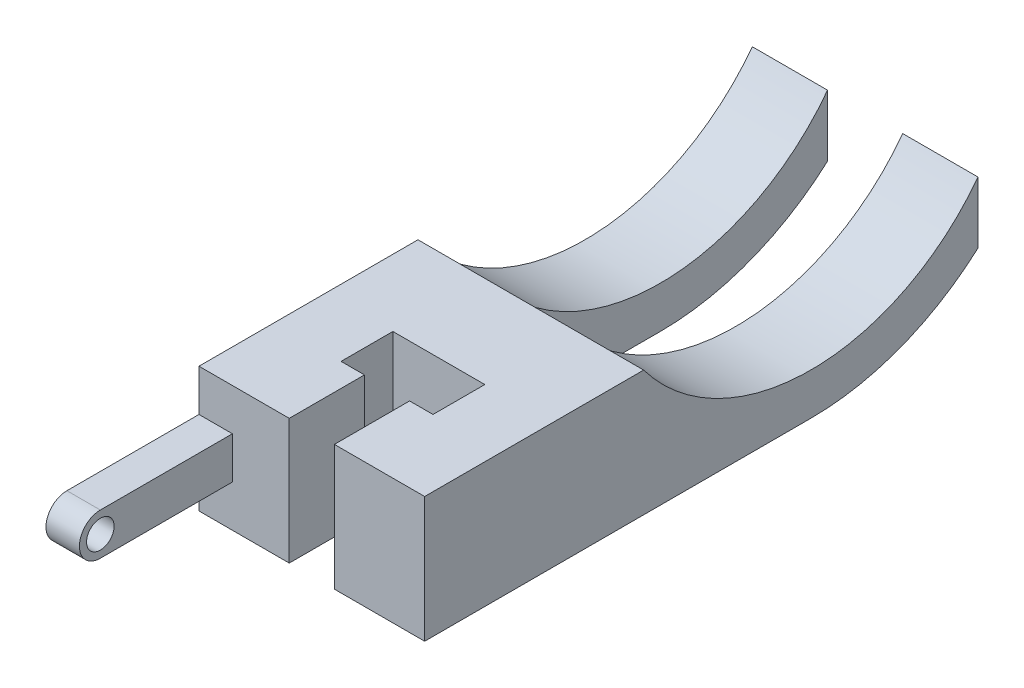
SolidWorks part; units mm, degrees
ref_plane "前视基准面" through (0, 0, 0) normal (0, 0, 1) x (1, 0, 0)
ref_plane "上视基准面" through (0, 0, 0) normal (0, 1, 0) x (1, 0, 0)
ref_plane "右视基准面" through (0, 0, 0) normal (1, 0, 0) x (0, 0, -1)
sketch "草图1" plane through (0, 0, 0) normal (0, 1, 0) x (1, 0, 0)
  line L0 (-5.5, 0) -> (5.5, 0)
  line L1 (5.5, 0) -> (5.5, -6.2)
  line L2 (5.5, -6.2) -> (2.7, -6.2)
  line L3 (2.7, -6.2) -> (2.7, -9.2)
  line L4 (2.7, -9.2) -> (5.5, -9.2)
  line L5 (5.5, -9.2) -> (5.5, -17)
  line L6 (5.5, -17) -> (8.5, -17)
  line L8 (-8.5, 3) -> (8.5, 3)
  line L9 (8.5, 3) -> (8.5, -17)
  line L10 (-5.5, -17) -> (-8.5, -17)
  line L11 (-5.5, -9.2) -> (-5.5, -17)
  line L12 (-2.7, -9.2) -> (-5.5, -9.2)
  line L13 (-2.7, -6.2) -> (-2.7, -9.2)
  line L14 (-5.5, -6.2) -> (-2.7, -6.2)
  line L15 (-5.5, 0) -> (-5.5, -6.2)
  line L16 (-8.5, 3) -> (-8.5, -17)
extrude "凸台-拉伸2" add sketch "草图1" along normal blind 15
sketch "草图2" plane through (8.5, 0, 0) normal (1, 0, 0) x (0, 0, -1)
  line L0 (-17, 15) -> (-17, 10)
  line L1 (-17, 15) -> (-17, 0) construction
  line L2 (-17, 0) -> (-17, 5)
  line L3 (-17, 15) -> (-9.2, 15)
  line L4 (-17, 15) -> (3, 15) construction
  line L5 (-9.2, 15) -> (-9.2, 10)
  line L6 (-9.2, 10) -> (-17, 10)
  line L7 (-17, 5) -> (-9.2, 5)
  line L8 (-9.2, 5) -> (-9.2, 0)
  line L9 (-17, 0) -> (3, 0) construction
  line L10 (-9.2, 0) -> (-17, 0)
extrude "切除-拉伸1" cut sketch "草图2" against normal blind 23
sketch "草图3" plane through (-8.5, 0, 0) normal (-1, 0, 0) x (0, 0, 1)
  line L0 (-3, 15) -> (-3, 7.5)
  line L1 (-3, 15) -> (-3, 0) construction
  line L2 (-3, 7.5) -> (15, 7.5)
  circle A0 centre (15, 7.5) radius 1.65
extrude "切除-拉伸2" cut sketch "草图3" against normal blind 23
sketch "草图4" plane through (0, 0, 17) normal (0, 0, 1) x (1, 0, 0)
  line L0 (-8.5, 10) -> (-5.5, 10)
  line L1 (-8.5, 10) -> (-8.5, 5.005)
  line L2 (-5.5, 10) -> (-5.5, 5.005)
  line L3 (-8.5, 5.005) -> (-5.5, 5.005)
  line L4 (-5.5, 10) -> (-5.5, 5) construction
  line L5 (-8.5, 10) -> (-5.5, 10) construction
  line L6 (5.5, 10) -> (8.5, 10)
  line L7 (5.5, 10) -> (5.5, 4.9814)
  line L8 (8.5, 10) -> (8.5, 4.9814)
  line L9 (5.5, 4.9814) -> (8.5, 4.9814)
extrude "凸台-拉伸3" add sketch "草图4" along normal blind 0.5
sketch "草图5" plane through (-8.5, 0, 0) normal (-1, 0, 0) x (0, 0, 1)
  line L0 (15, 10) -> (17.5, 10)
  line L1 (17.5, 10) -> (17.5, 7.5)
  line L2 (17.5, 7.5) -> (17.5, 5.005)
  line L3 (17.5, 5.005) -> (15, 5)
  line L4 (17.5, 5.005) -> (17.7329, 2.2884)
  line L5 (17.7329, 2.2884) -> (15, 5)
  circle A0 centre (15, 7.5) radius 2.5
extrude "切除-拉伸4" cut sketch "草图5" against normal blind 20.5
sketch "草图7" plane through (-8.5, 0, 0) normal (-1, 0, 0) x (0, 0, 1)
  line L0 (-3, 15) -> (-3, 0)
  line L1 (-3, 0) -> (-18, 0)
  line L2 (-18, 0) -> (-3, 15)
extrude "凸台-拉伸4" add sketch "草图7" against normal blind 17
sketch "草图8" plane through (0, 15, 0) normal (0, 1, 0) x (1, 0, 0)
  line L0 (-8.5, 3) -> (-8.5, 5)
  line L1 (-8.5, 3) -> (-8.5, 18) construction
  line L2 (-8.5, 5) -> (-6.5, 5)
  line L3 (-6.5, 5) -> (-6.5, 18)
  line L4 (-6.5, 5) -> (8.5, 5)
  line L5 (8.5, 3) -> (8.5, 18) construction
  line L6 (8.5, 5) -> (6.5, 5)
  line L7 (6.5, 5) -> (6.5, 18)
  line L8 (6.5, 18) -> (-6.5, 18)
extrude "切除-拉伸5" cut sketch "草图8" against normal blind 14 contours L7 L8 L3 L4
sketch "草图9" plane through (0, 1, 0) normal (0, 1, 0) x (1, 0, 0)
  line L0 (0, 5) -> (0, 8)
  line L1 (-6.5, 5) -> (6.5, 5) construction
  line L2 (0, 8) -> (-4, 8)
  circle A0 centre (-4, 8) radius 1.65
  circle A1 centre (4, 8) radius 1.65
  circle A2 centre (-4, 14) radius 1.65
  circle A3 centre (4, 14) radius 1.65
  dimension "D1" = 2
extrude "切除-拉伸6" cut sketch "草图9" against normal blind 14
sketch "草图10" plane through (-8.5, 0, 0) normal (-1, 0, 0) x (0, 0, 1)
  line L0 (15, 10) -> (25, 10)
  line L2 (15, 5) -> (25, 5)
  line L3 (25, 5) -> (25, 10)
  line L4 (15, 10) -> (15, 5)
  circle A0 centre (25, 7.5) radius 2.5
  circle A1 centre (25, 7.5) radius 1.65
  circle M1 centre (15, 7.5) radius 1.65
  arc M3 (15, 5) -> (15, 10) centre (15, 7.5) ccw
extrude "凸台-拉伸8" add sketch "草图10" along normal mid plane 50 contours A1 L3 A0 | A1 L3 A0 | A0 L0 L2 M3 | L4 M3 M1 | L4 M1 | L4 M1
sketch "草图11" plane through (0, 10, 0) normal (0, 1, 0) x (1, 0, 0)
  line L0 (-8.5, -15) -> (-16.5, -15)
  line L1 (-33.5, -15) -> (-8.5, -15) construction
  line L2 (-8.5, -15) -> (-8.5, -35.0128)
  line L3 (-8.5, -15) -> (-16.7588, -15)
  line L4 (-8.5, -35.0128) -> (-16.7588, -35.0128)
  line L5 (-16.7588, -15) -> (-16.7588, -35.0128)
  line L6 (-16.7588, -35.0128) -> (-38.7573, -35.0128)
  line L7 (-16.7588, -35.0128) -> (-16.7588, 0.8187)
  line L8 (-38.7573, -35.0128) -> (-38.7573, 0.8187)
  line L9 (-16.7588, 0.8187) -> (-38.7573, 0.8187)
  line M3 (-8.5, -15) -> (-33.5, -15)
  line M4 (-33.5, -15) -> (-33.5, -25)
  line M5 (-33.5, -25) -> (16.5, -25)
extrude "切除-拉伸8" cut sketch "草图11" against normal blind 50 contours L7 L9 L8 L6 L5 M5 M4 M3 | L5 M3 M4 M5
sketch "草图13" plane through (8.5, 0, 0) normal (1, 0, 0) x (0, 0, -1)
  line L0 (18, 0) -> (-9.2, 0)
  line L1 (-9.2, 0) -> (-9.2, 5)
  line L2 (-9.2, 5) -> (-15, 5)
  line L3 (-15, 5) -> (-15, 10)
  line L4 (-15, 10) -> (-9.2, 10)
  line L5 (-9.2, 10) -> (-9.2, 15)
  line L6 (-9.2, 15) -> (3, 15)
  line L7 (3, 15) -> (18, 0)
extrude "凸台-拉伸9" add sketch "草图13" along normal blind 8
sketch "草图14" plane through (-8.5, 0, 0) normal (-1, 0, 0) x (0, 0, 1)
  line L0 (15, 10) -> (15, 5)
  line L1 (9.2, 5) -> (15, 5) construction
  line L2 (15, 5) -> (9.2, 5)
  line L3 (9.2, 5) -> (9.2, 0)
  line L4 (9.2, 0) -> (-18, 0)
  line L5 (-18, 0) -> (-3, 15)
  line L6 (-3, 15) -> (9.2, 15)
  line L7 (9.2, 15) -> (9.2, 10)
  line L8 (9.2, 10) -> (15, 10)
extrude "凸台-拉伸11" add sketch "草图14" along normal blind 8
sketch "草图15" plane through (0, 10, 0) normal (0, 1, 0) x (1, 0, 0)
  line L0 (-5.5, -15) -> (-13.5, -15)
  line L1 (-13.5, -15) -> (-13.5, -9.2)
  line L2 (-16.5, -9.2) -> (-5.5, -9.2) construction
  line L3 (5.5, -15) -> (13.5, -15)
  line L4 (13.5, -15) -> (13.5, -9.2)
  line L5 (5.5, -9.2) -> (16.5, -9.2) construction
  line L6 (13.5, -9.2) -> (-13.5, -9.2)
  line L7 (5.5, -15) -> (-5.5, -15)
extrude "切除-拉伸9" cut sketch "草图15" against normal blind 8
sketch "草图16" plane through (0, 0, 15) normal (0, 0, -1) x (-1, 0, 0)
  line L4 (16.7588, 10) -> (16.7588, 5)
  line L5 (16.7588, 10) -> (16.5026, 10)
  line L6 (16.7588, 5) -> (16.5026, 5)
  line L7 (16.5026, 10) -> (16.5026, 5)
extrude "切除-拉伸11" cut sketch "草图16" against normal mid plane 80
sketch "草图18" plane through (-13.5, 0, 0) normal (1, 0, 0) x (0, 0, -1)
  line L0 (-9.2, 5) -> (-9.2, 10)
  line L1 (-9.2, 5) -> (-14.9767, 5)
  line L2 (-9.2, 10) -> (-14.9767, 10)
  line L3 (-14.9767, 5) -> (-14.9767, 10)
extrude "凸台-拉伸13" add sketch "草图18" along normal blind 29
sketch "草图19" plane through (0, 5, 0) normal (0, -1, 0) x (1, 0, 0)
  line L0 (0, 9.2) -> (-10, 9.2)
  line L1 (2.7, 9.2) -> (-2.7, 9.2) construction
  line L2 (-16.5, 9.2) -> (-2.7, 9.2) construction
  line L3 (0, 9.2) -> (10, 9.2)
  line L4 (2.7, 9.2) -> (16.5, 9.2) construction
  line L5 (10, 9.2) -> (10, 29.3376)
  line L7 (-10, 29.3376) -> (10, 29.3376)
  line L8 (-10, 29.3376) -> (-10, 9.2)
extrude "切除-拉伸13" cut sketch "草图19" against normal blind 24
sketch "草图20" plane through (0, 0, 0) normal (0, -1, 0) x (1, 0, 0)
  line L0 (-16.5, 9.2) -> (-13.5, 9.2)
  line L1 (-16.5, 9.2) -> (-2.7, 9.2) construction
  line L2 (16.5, 9.2) -> (13.5, 9.2)
  line L3 (2.7, 9.2) -> (16.5, 9.2) construction
  line L4 (13.5, 9.2) -> (13.5, -18)
  line L5 (16.5, -18) -> (-16.5, -18) construction
  line L6 (13.5, -18) -> (16.5, -18)
  line L7 (16.5, -18) -> (16.5, 42.2455)
  line L8 (16.5, 42.2455) -> (13.5, 42.2455)
  line L9 (13.5, 42.2455) -> (13.5, 9.2)
  line L10 (-13.5, 9.2) -> (-13.5, 43.5506)
  line L11 (-13.5, 43.5506) -> (-16.5, 43.5506)
  line L12 (-16.5, 43.5506) -> (-16.5, -18)
  line L13 (-16.5, -18) -> (-16.5, 9.2) construction
  line L14 (-16.5, -18) -> (-13.5, -18)
  line L15 (-13.5, -18) -> (-13.5, 9.2)
  line L16 (16.5, 42.2455) -> (39.5508, 38.5955)
  line L17 (39.5508, 38.5955) -> (42.4056, -22.5054)
  line L18 (42.4056, -22.5054) -> (16.5, -18)
  line L19 (-16.5, 43.5506) -> (-30.1917, 43.5506)
  line L20 (-30.1917, 43.5506) -> (-32.6273, -13.9343)
  line L21 (-32.6273, -13.9343) -> (-16.5, -18)
  line M4 (-2.7, 9.2) -> (-16.5, 9.2)
  line M5 (-16.5, 9.2) -> (-16.5, -18)
  line M6 (-16.5, -18) -> (16.5, -18)
  line M7 (16.5, -18) -> (16.5, 9.2)
  line M8 (16.5, 9.2) -> (2.7, 9.2)
extrude "切除-拉伸16" cut sketch "草图20" against normal through all contours L18 L17 L16 L7 M7 | L8 L9 L7 M8 | L4 M8 M6 M7 | L11 L12 L10 M4 | L15 M6 M4 M5 | L20 L21 L12 L19 M5
sketch "草图21" plane through (0, 5, 0) normal (0, -1, 0) x (1, 0, 0)
  line L0 (-13.5, 9.2) -> (-10, 9.2)
  line L1 (-13.5, 9.2) -> (-13.5, 28.5646)
  line L2 (-10, 9.2) -> (-10, 28.5646)
  line L3 (-13.5, 28.5646) -> (-10, 28.5646)
extrude "切除-拉伸17" cut sketch "草图21" against normal blind 10
sketch "草图22" plane through (13.5, 0, 0) normal (1, 0, 0) x (0, 0, -1)
  circle A0 centre (-25, 7.5) radius 1.65
extrude "凸台-拉伸14" add sketch "草图22" against normal blind 3.5
sketch "草图23" plane through (13.5, 0, 0) normal (1, 0, 0) x (0, 0, -1)
  line L0 (-9.2, 5) -> (-9.2, 10)
  line L1 (-9.2, 10) -> (-9.2, 7.5)
  line L2 (-9.2, 7.5) -> (-21, 7.5)
  line L3 (-21, 5) -> (-28.428, 0)
  line L4 (-28.428, 0) -> (-29.4139, 12.6342)
  line L5 (-29.4139, 12.6342) -> (-21, 10)
  circle A0 centre (-21, 7.5) radius 1.65
  circle A1 centre (-21, 7.5) radius 2.5
extrude "切除-拉伸18" cut sketch "草图23" against normal blind 3.5
sketch "草图24" plane through (0, 0, 9.2) normal (0, 0, 1) x (1, 0, 0)
  line L0 (13.5, 5) -> (13.5, 10)
  line L1 (13.5, 5) -> (10, 5)
  line L2 (13.5, 10) -> (10, 10)
  line L3 (10, 5) -> (10, 10)
extrude "凸台-拉伸16" add sketch "草图24" along normal blind 8
sketch "草图25" plane through (13.5, 0, 0) normal (1, 0, 0) x (0, 0, -1)
  line L0 (-9.2, 5) -> (-9.2, 10)
  line L2 (-31, 5) -> (-9.2, 5)
  line L3 (-9.2, 10) -> (-31, 10)
  circle A1 centre (-31, 7.5) radius 1.65
  arc A2 (-31, 10) -> (-31, 5) centre (-31, 7.5) ccw
extrude "凸台-拉伸17" add sketch "草图25" against normal blind 4
sketch "草图26" plane through (13.5, 0, 0) normal (1, 0, 0) x (0, 0, -1)
  line L0 (3, 15) -> (3, 0)
  line L1 (3, 15) -> (35.723, 15)
  line L2 (3, 0) -> (35.723, 0)
  line L3 (35.723, 15) -> (35.723, 0)
  line L4 (-9.2, 0) -> (18, 0) construction
extrude "切除-拉伸19" cut sketch "草图26" against normal blind 60
sketch "草图27" plane through (-13.5, 0, 0) normal (-1, 0, 0) x (0, 0, 1)
  line L0 (-3, 15) -> (-23, 15)
  line L1 (-23, 15) -> (-23, 30)
  line L2 (-23, 30) -> (-3, 15)
  line L3 (-23, 15) -> (-43, 15)
  line L4 (-43, 15) -> (-23, 30)
  line L5 (-3, 0) -> (-43, 0)
  line L6 (-43, 0) -> (-43, 15)
  circle A0 centre (-23, 30) radius 25
  line M4 (-3, 15) -> (-3, 0)
extrude "凸台-拉伸18" add sketch "草图27" against normal blind 9 contours A0 L6 L5 M4
sketch "草图28" plane through (13.5, 0, 0) normal (1, 0, 0) x (0, 0, -1)
  line L0 (3, 0) -> (43, 0)
  line L1 (43, 0) -> (43, 15)
  line L2 (43, 15) -> (3, 15)
  line L3 (3, 15) -> (3, 0)
  circle A0 centre (23, 30) radius 25
  line M2 (3, 0) -> (3, 15)
extrude "凸台-拉伸19" add sketch "草图28" against normal blind 9 contours A0 L0 L1 M2
sketch "草图29" plane through (0, 0, 9.2) normal (0, 0, 1) x (1, 0, 0)
  line L0 (13.5, 0) -> (2.7, 0)
  line L1 (13.5, 0) -> (13.5, 15)
  line L2 (2.7, 0) -> (2.7, 15)
  line L3 (13.5, 15) -> (2.7, 15)
  line L4 (2.7, 0) -> (13.5, 0) construction
  line L6 (-2.7, 15) -> (-2.7, 0)
  line L7 (-2.7, 15) -> (-13.5, 15)
  line L8 (-2.7, 0) -> (-13.5, 0)
  line L9 (-13.5, 15) -> (-13.5, 0)
extrude "凸台-拉伸20" add sketch "草图29" along normal blind 6
sketch "草图30" plane through (-13.5, 0, 0) normal (-1, 0, 0) x (0, 0, 1)
  line L0 (-3, 15) -> (-3, 0)
  line L1 (-3, 15) -> (-43.2251, 15)
  line L2 (-3, 0) -> (-43.2251, 0)
  line L3 (-43.2251, 15) -> (-43.2251, 0)
  line L4 (-43, 0) -> (15.2, 0) construction
extrude "切除-拉伸20" cut sketch "草图30" against normal blind 46
sketch "草图31" plane through (-13.5, 0, 0) normal (-1, 0, 0) x (0, 0, 1)
  line L0 (-3, 0) -> (-3, 15)
  line L1 (-3, 15) -> (-11, 15)
  line L3 (-11, 0) -> (-3, 0)
  line L5 (-11, 0) -> (-31, 0)
  line L6 (-31, 0) -> (-31, 5)
  line L9 (-51, 15) -> (-51, 7.6393)
  arc A0 (-51, 15) -> (-11, 15) centre (-31, 30) ccw
  arc A1 (-51, 7.6393) -> (-31, 0) centre (-31, 30) ccw
  line M4 (-3, 15) -> (-3, 0)
extrude "凸台-拉伸21" add sketch "草图31" against normal blind 9 contours A0 L6 L5 L3 L1 M4 | L9 A1 L6 A0
sketch "草图32" plane through (13.5, 0, 0) normal (1, 0, 0) x (0, 0, -1)
  line L0 (3, 0) -> (3, 15)
  line L1 (3, 15) -> (11, 15)
  line L2 (3, 0) -> (31, 0)
  line L3 (51, 15) -> (51, 7.6393)
  arc A0 (11, 15) -> (51, 15) centre (31, 30) ccw
  arc A1 (31, 0) -> (51, 7.6393) centre (31, 30) ccw
extrude "凸台-拉伸22" add sketch "草图32" against normal blind 9
sketch "草图33" plane through (0, 0, -3) normal (0, 0, -1) x (-1, 0, 0)
  line L0 (4.5, 0) -> (4.5, 15)
  line L1 (4.5, 0) -> (-4.5, 0)
  line L2 (4.5, 15) -> (-4.5, 15)
  line L3 (-4.5, 0) -> (-4.5, 15)
extrude "凸台-拉伸24" add sketch "草图33" along normal blind 8
sketch "草图34" plane through (-13.5, 0, 0) normal (-1, 0, 0) x (0, 0, 1)
  line L0 (31, 10) -> (15.2, 10)
  line L1 (15.2, 10) -> (15.2, 5)
  line L2 (15.2, 5) -> (31, 5)
  circle A0 centre (31, 7.5) radius 1.65
  arc A1 (31, 5) -> (31, 10) centre (31, 7.5) ccw
extrude "凸台-拉伸25" add sketch "草图34" against normal blind 4
sketch "草图35" plane through (13.5, 0, 0) normal (1, 0, 0) x (0, 0, -1)
  line L0 (-15.2, 10) -> (-15.2, 5)
  line L1 (-15.2, 10) -> (-51.5515, 10)
  line L2 (-15.2, 5) -> (-51.5515, 5)
  line L3 (-51.5515, 10) -> (-51.5515, 5)
extrude "切除-拉伸21" cut sketch "草图35" against normal blind 4
